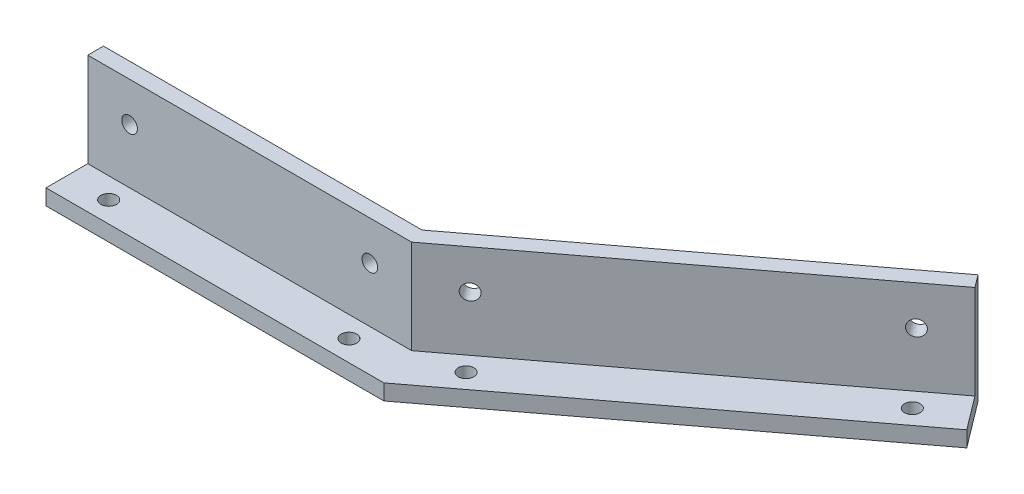
SolidWorks part; units mm, degrees
ref_plane "Alzado" through (0, 0, 0) normal (0, 0, 1) x (1, 0, 0)
ref_plane "Planta" through (0, 0, 0) normal (0, 1, 0) x (1, 0, 0)
ref_plane "Vista lateral" through (0, 0, 0) normal (1, 0, 0) x (0, 0, -1)
sketch "Croquis1" plane through (0, 0, 0) normal (0, 1, 0) x (1, 0, 0)
  line L0 (0, 0) -> (62, 0)
  line L1 (62, 0) -> (123.4499, 46.3994)
  line L2 (0, 0) -> (0, -8)
  line L3 (0, -8) -> (64.6811, -8)
  line L4 (64.6811, -8) -> (128.2706, 40.015)
  line L5 (128.2706, 40.015) -> (123.4499, 46.3994)
  dimension "D1" = 142.944
  dimension "D2" = 62
  dimension "D3" = 77
  dimension "D4" = 8
  dimension "D5" = 8
extrude "Saliente-Extruir1" add sketch "Croquis1" along normal blind 3
sketch "Croquis2" plane through (0, 3, 0) normal (0, 1, 0) x (1, 0, 0)
  line L0 (62, 0) -> (0, 0) construction
  circle A0 centre (8, -4) radius 1.5
  circle A1 centre (54, -4) radius 1.5
  dimension "D1" = 4
  dimension "D2" = 4
  dimension "D3" = 8
  dimension "D4" = 46
extrude "Cortar-Extruir1" cut sketch "Croquis2" against normal blind 3
sketch "Croquis3" plane through (0, 3, 0) normal (0, 1, 0) x (1, 0, 0)
  line L0 (62, 0) -> (64.4104, -3.1922) construction
  line L1 (123.4499, 46.3994) -> (62, 0) construction
  circle A0 centre (70.7948, 1.6285) radius 1.5
  circle A1 centre (119.4759, 38.3865) radius 1.5
  dimension "D1" = 90
  dimension "D2" = 4
  dimension "D3" = 4
  dimension "D4" = 8
  dimension "D5" = 4
  dimension "D6" = 61
extrude "Cortar-Extruir2" cut sketch "Croquis3" against normal blind 3
sketch "Croquis4" plane through (0, 3, 0) normal (0, 1, 0) x (1, 0, 0)
  line L0 (0, 0) -> (0, 3)
  line L1 (0, 3) -> (60.9946, 3)
  line L2 (123.4499, 46.3994) -> (121.6422, 48.7936)
  line L3 (121.6422, 48.7936) -> (60.9946, 3)
  line L4 (128.2706, 40.015) -> (123.4499, 46.3994) construction
  line L5 (123.4499, 46.3994) -> (62, 0) construction
  line L6 (0, 0) -> (62, 0)
  line L7 (62, 0) -> (123.4499, 46.3994)
  dimension "D1" = 180
  dimension "D2" = 0
  dimension "D3" = 3
  dimension "D4" = 3
extrude "Saliente-Extruir2" add sketch "Croquis4" against normal blind 3 and the other way blind 18
sketch "Croquis5" plane through (0, 0, 0) normal (0, 0, 1) x (1, 0, 0)
  line L0 (0, 21) -> (62, 21) construction
  line L1 (0, 21) -> (0, 3) construction
  line L2 (62, 21) -> (62, 3) construction
  circle A0 centre (8, 13.5) radius 1.5
  circle A1 centre (54, 13.5) radius 1.5
  dimension "D1" = 7.5
  dimension "D2" = 7.5
  dimension "D3" = 8
  dimension "D4" = 8
extrude "Cortar-Extruir3" cut sketch "Croquis5" against normal blind 3
sketch "Croquis6" plane through (22.5131, 0, 29.8156) normal (0.6026, 0, 0.7981) x (0.7981, 0, -0.6026)
  line L0 (49.4792, 21) -> (126.4792, 21) construction
  line L1 (49.4792, 21) -> (49.4792, 3) construction
  line L2 (126.4792, 21) -> (126.4792, 3) construction
  line L3 (126.4792, 3) -> (49.4792, 3) construction
  circle A0 centre (57.4792, 13.5) radius 1.5
  circle A1 centre (118.4792, 13.5) radius 1.5
  dimension "D1" = 7.5
  dimension "D2" = 8
  dimension "D3" = 8
  dimension "D4" = 7.5
  dimension "D5" = 10.5
  dimension "D6" = 61
extrude "Cortar-Extruir4" cut sketch "Croquis6" against normal blind 3
